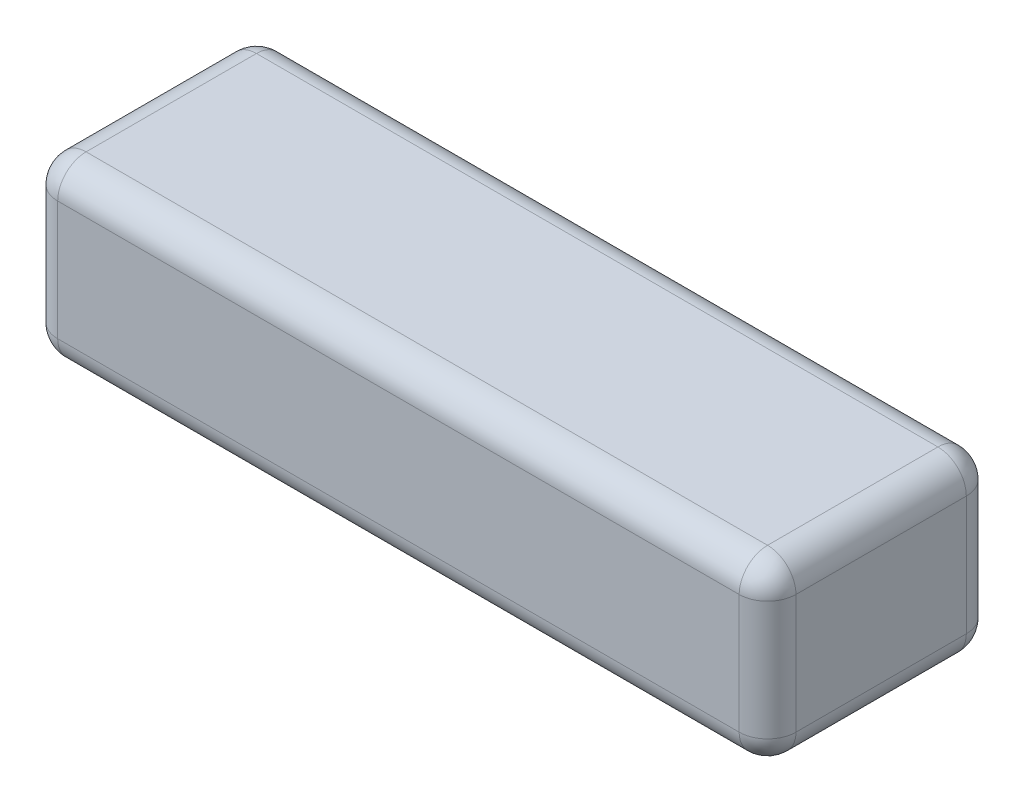
SolidWorks part; units mm, degrees
ref_plane "Front Plane" through (0, 0, 0) normal (0, 0, 1) x (1, 0, 0)
ref_plane "Top Plane" through (0, 0, 0) normal (0, 1, 0) x (1, 0, 0)
ref_plane "Right Plane" through (0, 0, 0) normal (1, 0, 0) x (0, 0, -1)
sketch "Sketch1" plane through (0, 0, 0) normal (0, 1, 0) x (1, 0, 0)
  line L1 (0, 40) -> (130, 40)
  line L2 (0, 40) -> (0, 0)
  line L3 (0, 0) -> (130, 0)
  line L4 (130, 40) -> (130, 0)
  dimension "D1" = 40
  dimension "D2" = 130
extrude "Boss-Extrude1" add sketch "Sketch1" along normal blind 31
fillet "Fillet1" radius 5 12 edges at (130, 0, -20) (0, 0, -20) (65, 0, 0) (65, 0, -40) (0, 15.5, -40) (0, 15.5, 0) (130, 15.5, 0) (130, 15.5, -40) (0, 31, -20) (65, 31, -40) (65, 31, 0) (130, 31, -20)
